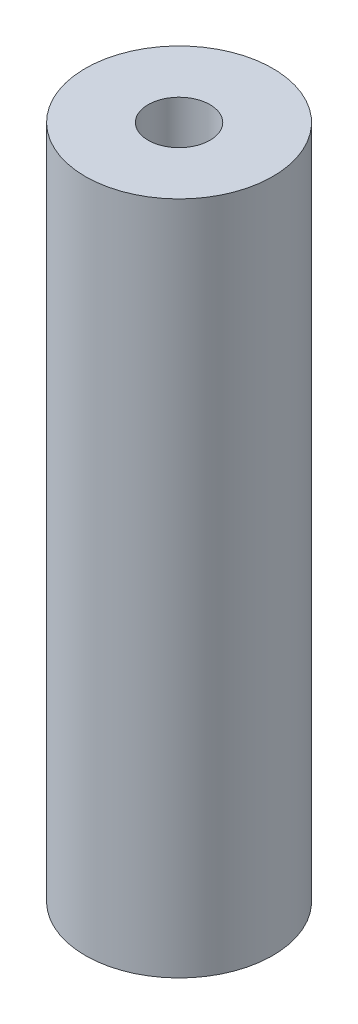
SolidWorks part; units mm, degrees
ref_plane "Спереди" through (0, 0, 0) normal (0, 0, 1) x (1, 0, 0)
ref_plane "Сверху" through (0, 0, 0) normal (0, 1, 0) x (1, 0, 0)
ref_plane "Справа" through (0, 0, 0) normal (1, 0, 0) x (0, 0, -1)
sketch "Эскиз1" plane through (0, 0, 0) normal (0, 1, 0) x (1, 0, 0)
  circle A0 centre (0, 0) radius 5
  circle A1 centre (0, 0) radius 1.65
  dimension "D1" = 10
  dimension "D2" = 3.3
extrude "Бобышка-Вытянуть1" add sketch "Эскиз1" along normal blind 36
